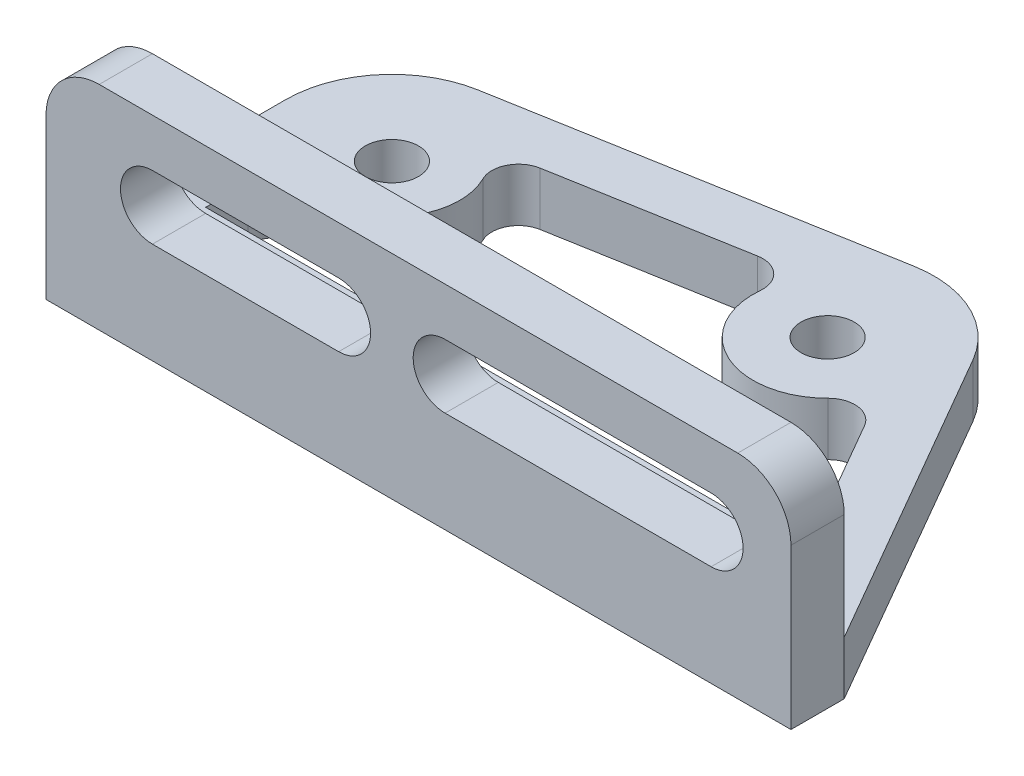
SolidWorks part; units mm, degrees
ref_plane "Front Plane" through (0, 0, 0) normal (0, 0, 1) x (1, 0, 0)
ref_plane "Top Plane" through (0, 0, 0) normal (0, 1, 0) x (1, 0, 0)
ref_plane "Right Plane" through (0, 0, 0) normal (1, 0, 0) x (0, 0, -1)
sketch "Sketch1" plane through (0, 0, 0) normal (0, 1, 0) x (1, 0, 0)
  line L0 (0, 0) -> (0, 35)
  line L1 (16.527, 54.6962) -> (86.1391, 66.9706)
  line L2 (106.9326, 57.2745) -> (140, 0)
  line L3 (140, 0) -> (0, 0)
  line L4 (122.6795, 10) -> (10, 10)
  line L5 (10, 10) -> (10, 17.9622)
  line L6 (35.0425, 47.8067) -> (69.8153, 53.938)
  line L7 (107.4418, 36.3925) -> (122.6795, 10)
  line L8 (18.2635, 44.8481) -> (87.8756, 57.1226) construction
  line L9 (10, 10) -> (10, 35) construction
  line L10 (98.2723, 52.2745) -> (122.6795, 10) construction
  arc A0 (0, 35) -> (16.527, 54.6962) centre (20, 35) cw
  arc A1 (86.1391, 66.9706) -> (106.9326, 57.2745) centre (89.6121, 47.2745) cw
  arc A4 (75.6625, 48.5564) -> (99.5607, 37.4125) centre (89.6121, 47.2745) ccw
  arc A5 (16.4079, 22.7598) -> (31.4305, 40.663) centre (20, 35) ccw
  arc A6 (10, 35) -> (18.2635, 44.8481) centre (20, 35) cw construction
  arc A7 (87.8756, 57.1226) -> (98.2723, 52.2745) centre (89.6121, 47.2745) cw construction
  circle A8 centre (20, 35) radius 5
  circle A9 centre (89.6121, 47.2745) radius 5
  arc A10 (99.5607, 37.4125) -> (107.4418, 36.3925) centre (103.1116, 33.8925) cw
  arc A11 (75.6625, 48.5564) -> (69.8153, 53.938) centre (70.6835, 49.014) ccw
  arc A12 (31.4305, 40.663) -> (35.0425, 47.8067) centre (35.9108, 42.8826) cw
  arc A13 (16.4079, 22.7598) -> (10, 17.9622) centre (15, 17.9622) ccw
  dimension "D1" = 20
  dimension "D7" = 10
  dimension "D8" = 10
  dimension "D9" = 5
  dimension "D2" = 140
  dimension "D3" = 60
  dimension "D4" = 10
  dimension "D5" = 35
  dimension "D6" = 10
extrude "Boss-Extrude1" add sketch "Sketch1" along normal blind 10 contours L2 L3 L0 A0 L1 A1
sketch "Sketch2" plane through (0, 10, 0) normal (0, 1, 0) x (1, 0, 0)
  line L1 (0, 0) -> (140, 0)
  line L2 (0, 0) -> (0, -10)
  line L3 (0, -10) -> (140, -10)
  line L4 (140, 0) -> (140, -10)
  point P6 (0, 0)
  point P7 (140, 0)
  dimension "D1" = 10
extrude "Boss-Extrude2" add sketch "Sketch2" along normal blind 30 and the other way blind 10
sketch "Sketch3" plane through (0, 0, 0) normal (0, 0, -1) x (-1, 0, 0)
  line L0 (-125, 25) -> (-75, 25) construction
  line L1 (-125, 31) -> (-75, 31)
  line L2 (-125, 19) -> (-75, 19)
  line L3 (-55, 25) -> (-20, 25) construction
  line L4 (-55, 31) -> (-20, 31)
  line L5 (-55, 19) -> (-20, 19)
  line L6 (-140, 10) -> (-140, 40) construction
  line L7 (-140, 0) -> (-106.9326, 0) construction
  arc A0 (-125, 31) -> (-125, 19) centre (-125, 25) ccw
  arc A1 (-75, 19) -> (-75, 31) centre (-75, 25) ccw
  arc A2 (-55, 31) -> (-55, 19) centre (-55, 25) ccw
  arc A3 (-20, 19) -> (-20, 31) centre (-20, 25) ccw
  point P2 (-100, 25)
  point P7 (-37.5, 25)
  dimension "D3" = 6
  dimension "D4" = 6
  dimension "D1" = 35
  dimension "D2" = 50
  dimension "D5" = 15
  dimension "D6" = 85
  dimension "D7" = 25
extrude "Cut-Extrude1" cut sketch "Sketch3" against normal blind 30 contours A3 L4 A2 L5
fillet "Fillet1" radius 10 2 edges at (140, 40, 5) (0, 40, 5)
